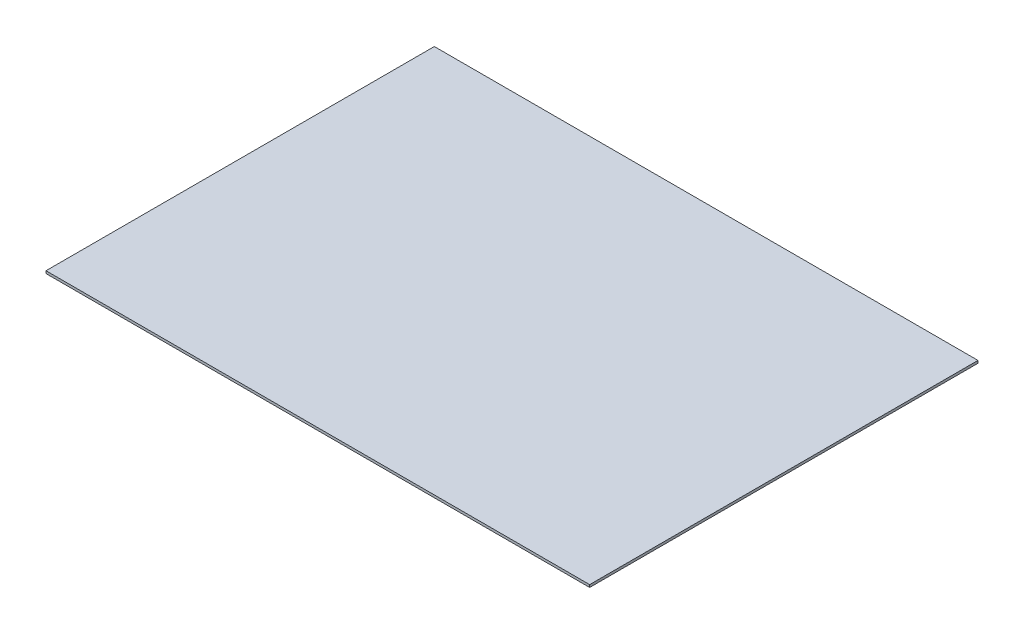
SolidWorks part; units mm, degrees
material "Glass"
ref_plane "Front Plane" through (0, 0, 0) normal (0, 0, 1) x (1, 0, 0)
ref_plane "Top Plane" through (0, 0, 0) normal (0, 1, 0) x (1, 0, 0)
ref_plane "Right Plane" through (0, 0, 0) normal (1, 0, 0) x (0, 0, -1)
sketch "Sketch1" plane through (0, 0, 0) normal (0, 1, 0) x (1, 0, 0)
  line L1 (350, -250) -> (-350, -250)
  line L2 (350, -250) -> (350, 250)
  line L3 (350, 250) -> (-350, 250)
  line L4 (-350, -250) -> (-350, 250)
  line L5 (350, -250) -> (-350, 250) construction
  line L6 (350, 250) -> (-350, -250) construction
  point P0 (0, 0)
  dimension "D1" = 500
  dimension "D2" = 700
extrude "Boss-Extrude1" add sketch "Sketch1" along normal blind 3.2
